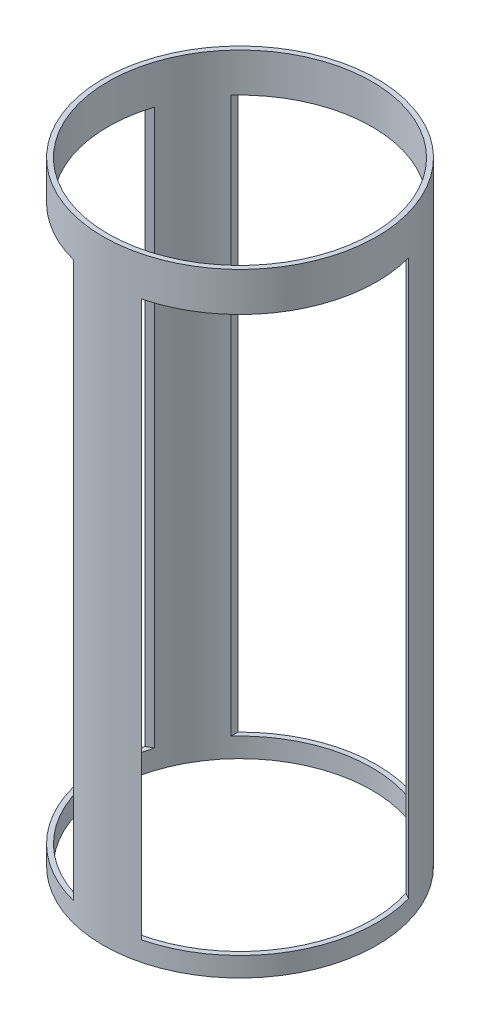
SolidWorks part; units mm, degrees
material "6061-T6 (SS)"
ref_plane "Front Plane" through (0, 0, 0) normal (0, 0, 1) x (1, 0, 0)
ref_plane "Top Plane" through (0, 0, 0) normal (0, 1, 0) x (1, 0, 0)
ref_plane "Right Plane" through (0, 0, 0) normal (1, 0, 0) x (0, 0, -1)
sketch "Sketch1" plane through (0, 0, 0) normal (0, 1, 0) x (1, 0, 0)
  circle A0 centre (0, 0) radius 88.9
  circle A1 centre (0, 0) radius 85.725
  dimension "D1" = 177.8
  dimension "D2" = 171.45
extrude "Boss-Extrude1" add sketch "Sketch1" along normal mid plane 398.78
sketch "Sketch2" plane through (0, 0, 0) normal (0, 0, 1) x (1, 0, 0)
  line L0 (85.725, 199.39) -> (-85.725, 199.39) construction
  line L1 (-63.5, -186.69) -> (63.5, -186.69)
  line L2 (-63.5, -186.69) -> (-63.5, 173.99)
  line L3 (-63.5, 173.99) -> (63.5, 173.99)
  line L4 (63.5, -186.69) -> (63.5, 173.99)
  line L5 (-63.5, -186.69) -> (63.5, 173.99) construction
  line L6 (-63.5, 173.99) -> (63.5, -186.69) construction
  line L7 (88.9, -199.39) -> (88.9, 199.39) construction
  line L8 (-88.9, 199.39) -> (-88.9, -199.39) construction
  line L9 (-88.9, -199.39) -> (88.9, -199.39) construction
  point P0 (0, 0)
  dimension "D1" = 25.4
  dimension "D2" = 25.4
  dimension "D3" = 25.4
  dimension "D4" = 12.7
extrude "Cut-Extrude1" cut sketch "Sketch2" against normal up to surface (62.217 mm away)
pattern_circular "CirPattern1" count 3 over 360 about axis through (0, 0, 0) along (0, 1, 0) of "Cut-Extrude1"
ref_plane "Plane1" through (88.9, 0, 0) normal (1, 0, 0) x (0, 0, -1)
sketch "Sketch3" plane through (88.9, 0, 0) normal (1, 0, 0) x (0, 0, -1)
  line L0 (23.8841, -186.69) -> (-86.1011, -186.69) construction
  line L1 (-88.9, -199.39) -> (88.9, -199.39) construction
  circle A0 centre (0, -195.58) radius 1.4351
  circle A1 centre (0, -193.04) radius 1.4351
  dimension "D1" = 3.81
  dimension "D2" = 2.8702
  dimension "D3" = 2.8702
  dimension "D4" = 6.35
extrude "Cut-Extrude2" [suppressed] cut sketch "Sketch3" against normal blind 15.24
pattern_circular "CirPattern2" [suppressed] count 12 over 360
sketch "Sketch4" plane through (88.9, 0, 0) normal (1, 0, 0) x (0, 0, -1)
  line L0 (0, 97.79) -> (0, -97.79) construction
  line L1 (88.9, 199.39) -> (-88.9, 199.39) construction
  circle A0 centre (0, 193.04) radius 1.4351
  dimension "D1" = 2.8702
  dimension "D2" = 6.35
extrude "Cut-Extrude3" [suppressed] cut sketch "Sketch4" against normal blind 15.24
pattern_circular "CirPattern3" [suppressed] count 12 over 360
ref_plane "Plane2" through (0, 0, 88.9) normal (0, 0, 1) x (1, 0, 0)
sketch "Sketch5" [suppressed] plane through (0, 0, 88.9) normal (0, 0, 1) x (1, 0, 0)
  circle A0 centre (0, 68.1736) radius 1.4351
  circle A1 centre (0, -60.5536) radius 1.4351
  circle A2 centre (0, 196.85) radius 1.4351 construction
  circle A3 centre (0, -189.23) radius 1.4351 construction
  dimension "D1" = 128.6764
  dimension "D2" = 128.6764
  dimension "D3" = 2.8702
  dimension "D4" = 2.8702
extrude "Cut-Extrude4" [suppressed] cut sketch "Sketch5" against normal blind 35.56
pattern_circular "CirPattern4" [suppressed] count 3 over 360
